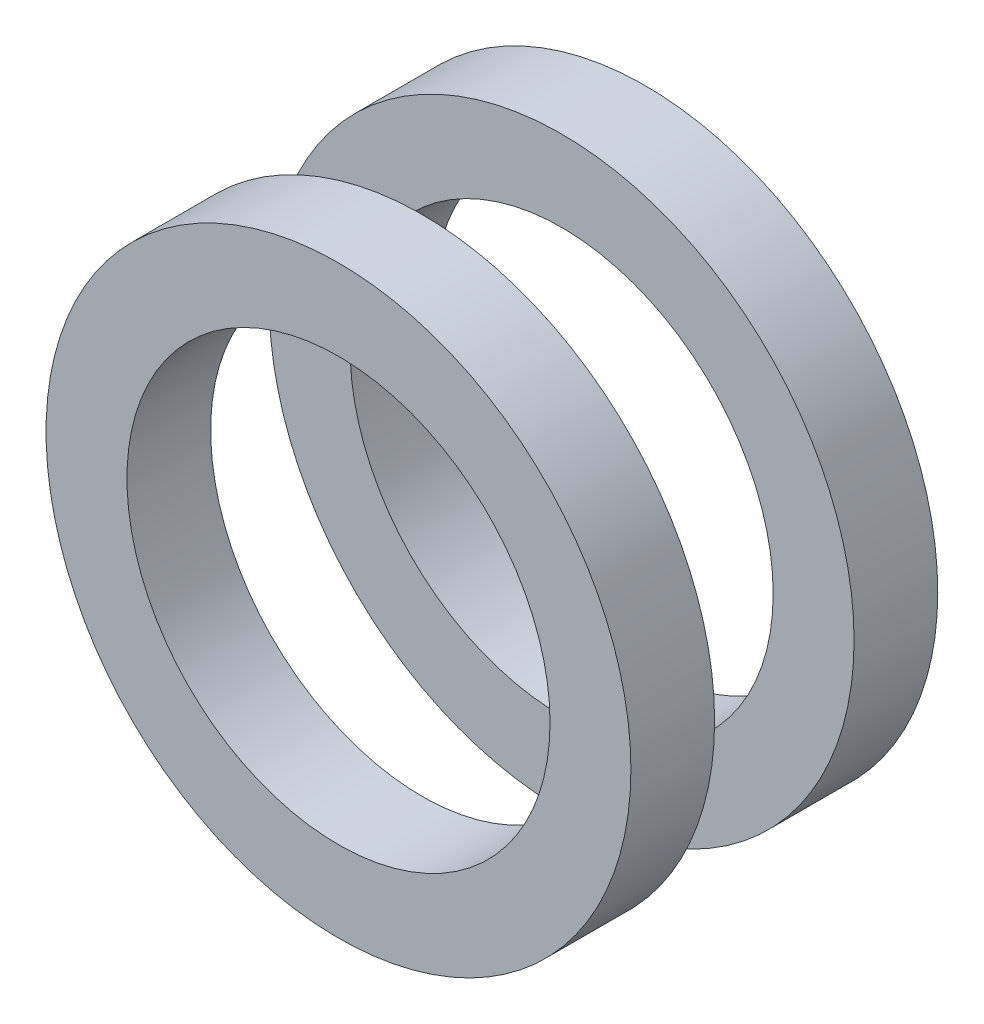
SolidWorks part; units mm, degrees
ref_plane "Спереди" through (0, 0, 0) normal (0, 0, 1) x (1, 0, 0)
ref_plane "Сверху" through (0, 0, 0) normal (0, 1, 0) x (1, 0, 0)
ref_plane "Справа" through (0, 0, 0) normal (1, 0, 0) x (0, 0, -1)
sketch "Эскиз1" plane through (0, 0, 0) normal (0, 0, 1) x (1, 0, 0)
  circle A0 centre (0, 0) radius 62.9
  circle A1 centre (0, 0) radius 45.5
extrude "Endturn_R" add sketch "Эскиз1" along normal blind 18 from offset 15 separate body
sketch "Эскиз2" plane through (0, 0, 0) normal (0, 0, 1) x (1, 0, 0)
  circle A0 centre (0, 0) radius 62.9
  circle A1 centre (0, 0) radius 45.5
extrude "Endturn_L" add sketch "Эскиз2" along normal blind 18 from offset 33 separate body
